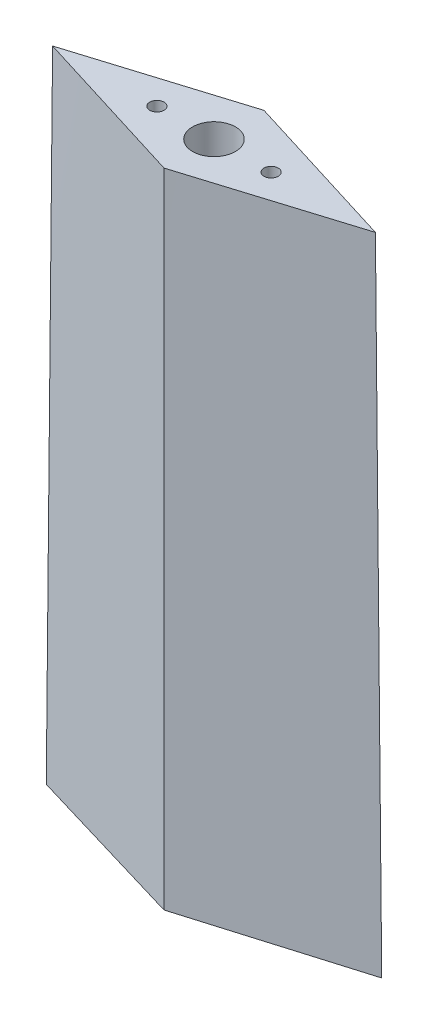
SolidWorks part; units mm, degrees
ref_plane "Front Plane" through (0, 0, 0) normal (0, 0, 1) x (1, 0, 0)
ref_plane "Top Plane" through (0, 0, 0) normal (0, 1, 0) x (1, 0, 0)
ref_plane "Right Plane" through (0, 0, 0) normal (1, 0, 0) x (0, 0, -1)
sketch "Sketch1" plane through (0, 0, 0) normal (0, 0, 1) x (1, 0, 0)
  line L0 (142.4212, 465.168) -> (219.716, 465.168)
  line L1 (219.716, 465.168) -> (213.5025, 1096.9676)
  line L2 (213.5025, 1096.9676) -> (181.0686, 1174.3372)
  line L3 (181.0686, 1174.3372) -> (148.6348, 1096.9676)
  line L4 (148.6348, 1096.9676) -> (142.4212, 465.168)
  point P2 (181.0686, 465.168)
extrude "Boss-Extrude1" add sketch "Sketch1" along normal blind 11.1125 and the other way blind 11.1125
sketch "Sketch2" plane through (0, 465.168, 0) normal (0, -1, 0) x (1, 0, 0)
  line L0 (142.4212, 0) -> (181.0686, 11.1125)
  line L1 (142.4212, -11.1125) -> (142.4212, 11.1125) construction
  line L2 (142.4212, 11.1125) -> (219.716, 11.1125) construction
  line L3 (181.0686, 11.1125) -> (219.716, 0)
  line L4 (219.716, -11.1125) -> (219.716, 11.1125) construction
  line L8 (142.4212, 0) -> (137.8486, 0)
  line L9 (137.8486, 0) -> (137.8486, 15.2584)
  line L10 (137.8486, 15.2584) -> (222.7051, 15.2584)
  line L11 (222.7051, 15.2584) -> (222.7051, 0)
  line L12 (222.7051, 0) -> (219.716, 0)
ref_plane "Plane1" through (0, 1096.9676, 0) normal (0, 1, 0) x (1, 0, 0)
sketch "Sketch3" plane through (0, 1096.9676, 0) normal (0, 1, 0) x (1, 0, 0)
  line L1 (148.6348, 11.1125) -> (148.6348, -11.1125) construction
  line L3 (213.5025, 11.1125) -> (213.5025, -11.1125) construction
  line L4 (213.5025, 0) -> (181.0686, -11.1125)
  line L5 (181.0686, -11.1125) -> (148.6348, 0)
  line L6 (148.6348, 0) -> (137.8486, 0)
  line L7 (137.8486, 0) -> (137.8486, -15.2584)
  line L8 (137.8486, -15.2584) -> (222.7051, -15.2584)
  line L9 (222.7051, -15.2584) -> (222.7051, 0)
  line L10 (222.7051, 0) -> (213.5025, 0)
loft "Cut-Loft1" cut profiles "Sketch2", "Sketch3"
mirror "Mirror1" about plane through (0, 0, 0) normal (0, 0, 1) of "Cut-Loft1"
ref_plane "Plane2" through (-32.1031, 13.4578, 93.6987) normal (-0.3212, 0.1346, 0.9374) x (0.947, 0.0457, 0.3179)
sketch "Sketch5" plane through (-32.1031, 13.4578, 93.6987) normal (-0.3212, 0.1346, 0.9374) x (0.947, 0.0457, 0.3179)
  line L1 (164.4105, 1280.8293) -> (274.288, 1280.8293)
  line L2 (164.4105, 1280.8293) -> (164.4105, 997.7782)
  line L3 (164.4105, 997.7782) -> (274.288, 997.7782)
  line L4 (274.288, 1280.8293) -> (274.288, 997.7782)
extrude "Cut-Extrude2" cut sketch "Sketch5" along normal through all
ref_plane "Plane3" through (69.4583, 29.1174, 202.7265) normal (0.3212, 0.1346, 0.9374) x (0.947, -0.0457, -0.3179)
sketch "Sketch6" plane through (69.4583, 29.1174, 202.7265) normal (0.3212, 0.1346, 0.9374) x (0.947, -0.0457, -0.3179)
  line L1 (57.1921, 1173.3831) -> (206.3136, 1173.3831)
  line L2 (57.1921, 1173.3831) -> (57.1921, 1064.4614)
  line L3 (57.1921, 1064.4614) -> (206.3136, 1064.4614)
  line L4 (206.3136, 1173.3831) -> (206.3136, 1064.4614)
extrude "Cut-Extrude3" cut sketch "Sketch6" along normal through all
mirror "Mirror2" about plane through (0, 0, 0) normal (0, 0, 1) of "Cut-Extrude2", "Cut-Extrude3"
sketch "Sketch7" plane through (0, 465.168, 0) normal (0, -1, 0) x (1, 0, 0)
  circle A0 centre (181.0686, 0) radius 4.7625
  dimension "D1" = 9.525
extrude "Cut-Extrude4" cut sketch "Sketch7" against normal blind 635
sketch "Sketch8" plane through (0, 0, 0) normal (0, 0, 1) x (1, 0, 0)
  line L0 (105.7103, 602.8372) -> (255.485, 602.8372)
  line L1 (105.7103, 1207.5881) -> (255.485, 1207.5881)
  line L2 (105.7103, 1207.5881) -> (105.7103, 454.0044)
  line L3 (105.7103, 454.0044) -> (255.485, 454.0044)
  line L4 (255.485, 1207.5881) -> (255.485, 454.0044)
  line L5 (255.485, 745.7122) -> (105.7103, 745.7122)
  line L6 (105.7103, 888.5872) -> (255.485, 888.5872)
  line L7 (255.485, 1031.4622) -> (105.7103, 1031.4622)
  dimension "D1" = 142.875
  dimension "D2" = 142.875
  dimension "D3" = 142.875
  dimension "D4" = 142.875
extrude "Cut-Extrude8" cut sketch "Sketch8" against normal through all and the other way through all contours L4 L0 L2 L3 | L6 L2 L5 L4 | L4 L7 L2 L6 | L7 L4 L1 L2
sketch "Sketch11" plane through (0, 745.7122, 0) normal (0, 1, 0) x (1, 0, 0)
  circle A0 centre (168.3686, 0) radius 1.5875
  circle A1 centre (193.7686, 0) radius 1.5875
  circle A2 centre (181.0686, 0) radius 4.7625 construction
  dimension "D1" = 12.7
  dimension "D2" = 12.7
  dimension "D3" = 3.175
extrude "Cut-Extrude9" cut sketch "Sketch11" against normal blind 12.7
sketch "Sketch12" plane through (0, 602.8372, 0) normal (0, -1, 0) x (1, 0, 0)
  circle A0 centre (168.3686, 0) radius 1.5875
  circle A1 centre (193.7686, 0) radius 1.5875
  circle A2 centre (181.0686, 0) radius 4.7625 construction
  dimension "D1" = 12.7
  dimension "D2" = 12.7
  dimension "D3" = 3.175
extrude "Cut-Extrude10" cut sketch "Sketch12" against normal blind 12.7
